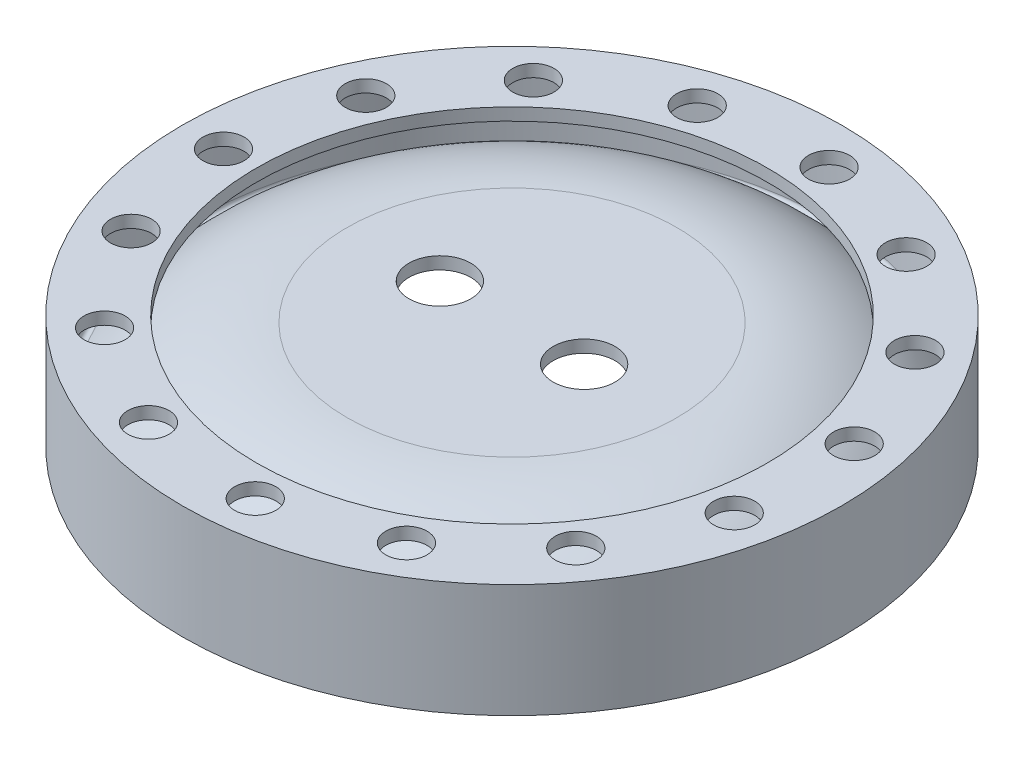
SolidWorks part; units mm, degrees
ref_plane "Front" through (0, 0, 0) normal (0, 0, 1) x (1, 0, 0)
ref_plane "Top" through (0, 0, 0) normal (0, 1, 0) x (1, 0, 0)
ref_plane "Right" through (0, 0, 0) normal (1, 0, 0) x (0, 0, -1)
sketch "Sketch1" plane through (0, 0, 0) normal (0, 0, 1) x (1, 0, 0)
  line L0 (0, 25.4) -> (0, 0) construction
  line L1 (-101.6, 0) -> (101.6, 0) construction
  line L2 (-101.6, 0) -> (-101.6, 25.4) construction
  line L3 (-101.6, 25.4) -> (101.6, 25.4) construction
  line L4 (101.6, 0) -> (101.6, 25.4) construction
  line L5 (0, 25.4) -> (50.8, 25.4)
  line L6 (97.79, 0) -> (97.79, 23.495)
  line L7 (97.79, 23.495) -> (78.74, 23.495)
  line L8 (0, 21.59) -> (50.8, 21.59)
  line L9 (101.6, -7.6776) -> (101.6, 27.305)
  line L10 (101.6, 27.305) -> (78.74, 27.305)
  line L11 (97.79, -7.6776) -> (101.6, -7.6776)
  line L12 (0, 25.4) -> (0, 21.59)
  line L13 (101.6, -18.0975) -> (101.6, 27.305) construction
  line L14 (78.74, 27.305) -> (78.74, 23.495)
  arc A0 (50.8, 25.4) -> (97.79, 0) centre (50.8, -30.7658) cw
  arc A1 (50.8, 21.59) -> (97.79, -7.6776) centre (50.8, -30.7658) cw
  arc A3 (50.8, 21.59) -> (101.6, -18.0975) centre (50.8, -30.7658) cw construction
  dimension "D1" = 203.2
  dimension "D2" = 25.4
  dimension "D3" = 50.8
  dimension "D4" = 3.81
  dimension "D5" = 3.81
  dimension "D6" = 19.05
  dimension "D7" = 3.81
revolve "Revolve1" add sketch "Sketch1" angle 360 about L0
sketch "Sketch2" plane through (0, 25.4, 0) normal (0, 1, 0) x (1, 0, 0)
  line L0 (-22.225, 0) -> (22.225, 0) construction
  circle A0 centre (-22.225, 0) radius 9.525
  circle A1 centre (22.225, 0) radius 9.525
  dimension "D2" = 19.05
  dimension "D1" = 44.45
extrude "Cut-Extrude1" cut sketch "Sketch2" against normal through all
sketch "Sketch3" plane through (0, 27.305, 0) normal (0, 1, 0) x (1, 0, 0)
  line L0 (0, 0) -> (-88.9, 0) construction
  circle A0 centre (-88.9, 0) radius 6.35
  dimension "D1" = 12.7
  dimension "D2" = 88.9
extrude "Cut-Extrude2" cut sketch "Sketch3" against normal up to surface (3.81 mm away) up to face at (0, 23.495, 97.79)
pattern_circular "CirPattern1" count 15 over 360 about axis through (0, 0, 0) along (0, 1, 0) of "Cut-Extrude2"
fillet "Fillet1" radius 1.27 2 edges at (0, 23.495, 97.79) (0, 0, 97.79)
